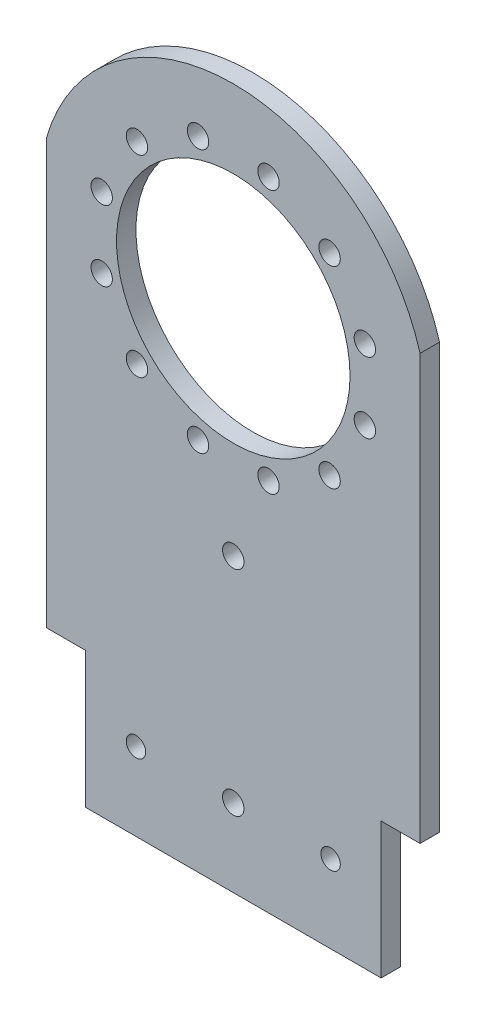
SolidWorks part; units mm, degrees
material "6061 合金"
ref_plane "前视基准面" through (0, 0, 0) normal (0, 0, 1) x (1, 0, 0)
ref_plane "上视基准面" through (0, 0, 0) normal (0, 1, 0) x (1, 0, 0)
ref_plane "右视基准面" through (0, 0, 0) normal (1, 0, 0) x (0, 0, -1)
other "Configuration Table"
sketch "草图1" plane through (0, 0, 0) normal (0, 0, 1) x (1, 0, 0)
  line L0 (0, 0) -> (0, 150.9585) construction
  line L3 (-48, 109.07) -> (-48, 0)
  line L4 (-48, 0) -> (48, 0)
  line L5 (48, 109.07) -> (48, 0)
  circle A0 centre (0, 95.07) radius 30
  arc A2 (48, 109.07) -> (-48, 109.07) centre (0, 95.07) ccw
  dimension "D3" = 60
  dimension "D4" = 50
  dimension "D1" = 96
  dimension "D2" = 95.07
extrude "凸台-拉伸1" add sketch "草图1" along normal blind 5
sketch "草图2" plane through (0, 0, 0) normal (0, -1, 0) x (1, 0, 0)
  line L0 (-53.8408, 2.5) -> (58.1589, 2.5) construction
  line L1 (0, 20.308) -> (0, -17.9139) construction
  line L2 (-48, 5) -> (48, 5) construction
  line L3 (-48, 0) -> (48, 0) construction
  circle A0 centre (35, 2.5) radius 2.75
  circle A1 centre (-35, 2.5) radius 2.75
  dimension "D2" = 5.5
  dimension "D1" = 70
extrude "切除-拉伸1" [suppressed] cut sketch "草图2" against normal blind 50
sketch "草图3" plane through (0, 0, 5) normal (0, 0, 1) x (1, 0, 0)
  line L0 (0, 0) -> (0, 95.092) construction
  circle A0 centre (0, 40) radius 2.75
  dimension "D1" = 5.5
  dimension "D2" = 40
extrude "切除-拉伸2" cut sketch "草图3" against normal blind 20
sketch "草图4" plane through (0, 0, 5) normal (0, 0, 1) x (1, 0, 0)
  line L0 (0, 95.07) -> (0, 148.0466) construction
  line L1 (0, 95.07) -> (15.7821, 153.9695) construction
  circle A0 centre (9.0587, 128.8774) radius 2.75
  circle A1 centre (24.7487, 119.8187) radius 2.75
  circle A2 centre (33.8074, 104.1287) radius 2.75
  circle A3 centre (33.8074, 86.0113) radius 2.75
  circle A4 centre (24.7487, 70.3213) radius 2.75
  circle A5 centre (9.0587, 61.2626) radius 2.75
  circle A6 centre (-9.0587, 61.2626) radius 2.75
  circle A7 centre (-24.7487, 70.3213) radius 2.75
  circle A8 centre (-33.8074, 86.0113) radius 2.75
  circle A9 centre (-33.8074, 104.1287) radius 2.75
  circle A10 centre (-24.7487, 119.8187) radius 2.75
  circle A11 centre (-9.0587, 128.8774) radius 2.75
  point P31 (0, 95.07)
  dimension "D1" = 5.5
  dimension "D2" = 35
  dimension "D3" = 15
  dimension "D4" = 12
extrude "切除-拉伸3" cut sketch "草图4" against normal blind 10
sketch "草图5" plane through (0, 0, 5) normal (0, 0, 1) x (1, 0, 0)
  line L0 (0, 0) -> (0, 169.4961) construction
  line L2 (-58, 0) -> (58, 0)
  line L3 (-58, 0) -> (-58, -50)
  line L4 (-58, -50) -> (58, -50)
  line L5 (58, 0) -> (58, -50)
  dimension "D1" = 116
  dimension "D2" = 50
extrude "碳板突出" [suppressed] add sketch "草图5" against normal up to surface (5 mm away)
sketch "草图6" [suppressed] plane through (0, 0, 5) normal (0, 0, 1) x (1, 0, 0)
  line L0 (0, 0) -> (0, -61.5724) construction
  line L2 (45, -5) -> (50.2, -5)
  line L3 (45, -5) -> (45, -20.2)
  line L4 (45, -20.2) -> (50.2, -20.2)
  line L5 (50.2, -5) -> (50.2, -20.2)
  line L6 (45, -30.2) -> (50.2, -30.2)
  line L7 (45, -30.2) -> (45, -45.4)
  line L8 (45, -45.4) -> (50.2, -45.4)
  line L9 (50.2, -30.2) -> (50.2, -45.4)
  line L10 (-50.2, -30.2) -> (-50.2, -45.4)
  line L11 (-45, -45.4) -> (-50.2, -45.4)
  line L12 (-45, -30.2) -> (-45, -45.4)
  line L13 (-45, -30.2) -> (-50.2, -30.2)
  line L14 (-50.2, -5) -> (-50.2, -20.2)
  line L15 (-45, -20.2) -> (-50.2, -20.2)
  line L16 (-45, -5) -> (-45, -20.2)
  line L17 (-45, -5) -> (-50.2, -5)
  line L18 (58, 0) -> (48, 0) construction
  dimension "D1" = 5.2
  dimension "D2" = 15.2
  dimension "D3" = 15.2
  dimension "D4" = 45
  dimension "D5" = 10
  dimension "D6" = 5
extrude "切除-拉伸4" [suppressed] cut sketch "草图6" against normal through all both
sketch "草图7" [suppressed] plane through (0, 0, 5) normal (0, 0, 1) x (1, 0, 0)
  line L0 (50.2, -20.2) -> (50.2, -5) construction
  line L1 (45, -5) -> (45, -20.2) construction
  line L2 (50.2, -45.4) -> (50.2, -30.2) construction
  line L3 (45, -30.2) -> (45, -45.4) construction
  line L4 (50.2, -5) -> (45, -5) construction
  line L5 (45, -20.2) -> (50.2, -20.2) construction
  line L6 (50.2, -30.2) -> (45, -30.2) construction
  line L7 (45, -45.4) -> (50.2, -45.4) construction
  line L8 (0, 0) -> (0, -72.6402) construction
  circle A0 centre (50.2, -6.55) radius 1.55
  circle A1 centre (50.2, -18.65) radius 1.55
  circle A2 centre (45, -6.55) radius 1.55
  circle A3 centre (45, -18.65) radius 1.55
  circle A4 centre (50.2, -31.75) radius 1.55
  circle A5 centre (45, -31.75) radius 1.55
  circle A6 centre (50.2, -43.85) radius 1.55
  circle A7 centre (45, -43.85) radius 1.55
  circle A8 centre (-45, -43.85) radius 1.55
  circle A9 centre (-50.2, -43.85) radius 1.55
  circle A10 centre (-45, -31.75) radius 1.55
  circle A11 centre (-50.2, -31.75) radius 1.55
  circle A12 centre (-45, -18.65) radius 1.55
  circle A13 centre (-45, -6.55) radius 1.55
  circle A14 centre (-50.2, -18.65) radius 1.55
  circle A15 centre (-50.2, -6.55) radius 1.55
  dimension "D1" = 3.1
extrude "切除-拉伸5" [suppressed] cut sketch "草图7" against normal through all both
sketch "草图8" [suppressed] plane through (0, 0, 5) normal (0, 0, 1) x (1, 0, 0)
  line L0 (0, 22.7135) -> (0, -60.4554) construction
  line L1 (58, -50) -> (58, 0) construction
  line L2 (58, -5) -> (63, -5)
  line L3 (58, -5) -> (58, -20)
  line L4 (58, -20) -> (63, -20)
  line L5 (63, -5) -> (63, -20)
  line L6 (58, 0) -> (48, 0) construction
  line L7 (58, -30) -> (63, -30)
  line L8 (58, -30) -> (58, -45)
  line L9 (58, -45) -> (63, -45)
  line L10 (63, -30) -> (63, -45)
  line L11 (-63, -30) -> (-63, -45)
  line L12 (-58, -45) -> (-63, -45)
  line L13 (-58, -30) -> (-58, -45)
  line L14 (-58, -30) -> (-63, -30)
  line L15 (-63, -5) -> (-63, -20)
  line L16 (-58, -20) -> (-63, -20)
  line L17 (-58, -5) -> (-58, -20)
  line L18 (-58, -5) -> (-63, -5)
  dimension "D1" = 5
  dimension "D2" = 15
  dimension "D3" = 5
  dimension "D4" = 10
  dimension "D5" = 15
extrude "碳板榫卯突起" [suppressed] add sketch "草图8" against normal up to surface (5 mm away)
sketch "草图9" [suppressed] plane through (0, 0, 5) normal (0, 0, 1) x (1, 0, 0)
  line L0 (58, -5) -> (58, 0) construction
  line L1 (58, -30) -> (58, -20) construction
  line L2 (58, -50) -> (58, -45) construction
  line L3 (63, -5) -> (58, -5) construction
  line L4 (58, -20) -> (63, -20) construction
  line L5 (63, -30) -> (58, -30) construction
  line L6 (58, -45) -> (63, -45) construction
  line L7 (0, 0) -> (0, -84.76) construction
  circle A0 centre (58, -3.45) radius 1.55
  circle A1 centre (58, -21.55) radius 1.55
  circle A2 centre (58, -28.45) radius 1.55
  circle A3 centre (58, -46.55) radius 1.55
  circle A4 centre (-58, -46.55) radius 1.55
  circle A5 centre (-58, -28.45) radius 1.55
  circle A6 centre (-58, -21.55) radius 1.55
  circle A7 centre (-58, -3.45) radius 1.55
  dimension "D1" = 3.1
extrude "碳板榫卯半圆" [suppressed] cut sketch "草图9" against normal up to surface (5 mm away)
fillet "碳板榫卯圆角" [suppressed] radius 5
sketch "草图10" plane through (0, 0, 5) normal (0, 0, 1) x (1, 0, 0)
  line L0 (0, 87.232) -> (0, -56.3055) construction
  line L1 (-48, 0) -> (48, 0) construction
  line L2 (-38, 0) -> (38, 0)
  line L3 (-38, 0) -> (-38, -34.93)
  line L4 (-38, -34.93) -> (38, -34.93)
  line L5 (38, 0) -> (38, -34.93)
  circle A0 centre (25, -14.93) radius 2.5
  circle A1 centre (-25, -14.93) radius 2.5
  circle A2 centre (0, -14.93) radius 2.75
  dimension "D3" = 5
  dimension "D6" = 5.5
  dimension "D1" = 76
  dimension "D2" = 34.93
  dimension "D4" = 20
  dimension "D5" = 50
extrude "凸台-拉伸2" add sketch "草图10" against normal up to surface (5 mm away) up to face at (27.4987, 119.8187, 0)
sketch "草图11" plane through (0, 0, 5) normal (0, 0, 1) x (1, 0, 0)
  line L0 (38, -34.93) -> (38, 0) construction
  line L1 (28, -15) -> (38, -15)
  line L2 (28, -15) -> (28, -35)
  line L3 (28, -35) -> (38, -35)
  line L4 (38, -15) -> (38, -35)
  line L5 (38, 0) -> (48, 0) construction
  line L6 (0, 0) -> (0, -149.1225) construction
  line L7 (-38, -15) -> (-38, -35)
  line L8 (-28, -35) -> (-38, -35)
  line L9 (-28, -15) -> (-28, -35)
  line L10 (-28, -15) -> (-38, -15)
  circle A0 centre (33, -10) radius 2.75
  circle A1 centre (23, -25) radius 2.75
  circle A2 centre (33, -40) radius 2.75
  circle A3 centre (-33, -40) radius 2.75
  circle A4 centre (-23, -25) radius 2.75
  circle A5 centre (-33, -10) radius 2.75
  dimension "D3" = 5.5
  dimension "D1" = 10
  dimension "D2" = 20
  dimension "D4" = 5
  dimension "D5" = 10
  dimension "D6" = 5
  dimension "D7" = 5
  dimension "D8" = 5
  dimension "D9" = 5
  dimension "D10" = 15
extrude "切除-拉伸6" [suppressed] cut sketch "草图11" against normal blind 10
fillet "圆角1" [suppressed] radius 2
